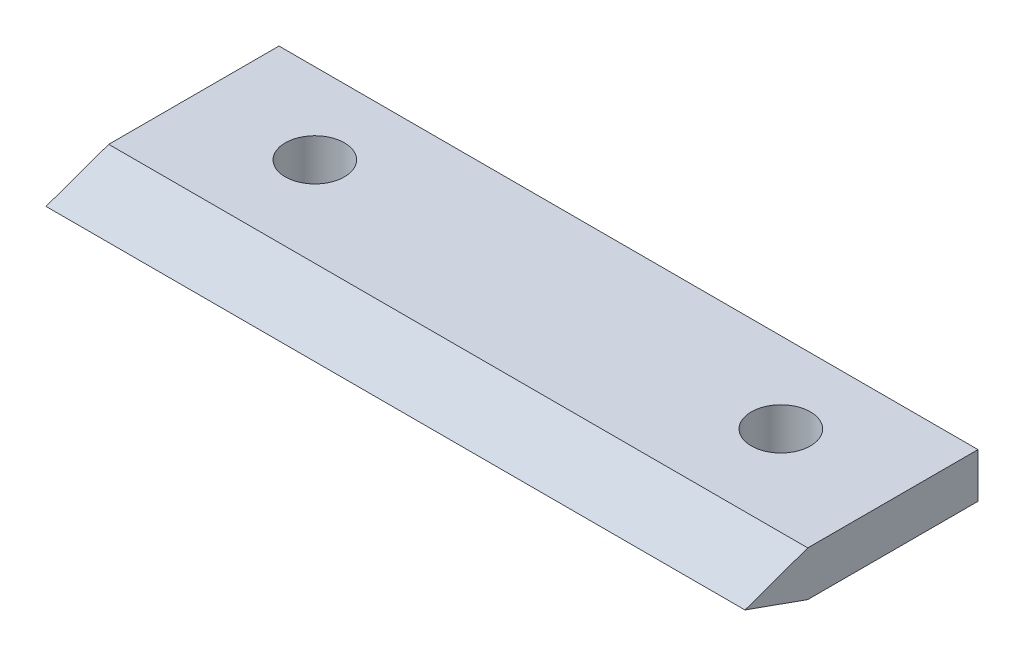
SolidWorks part; units mm, degrees
material "AISI 类型 A2 刀具钢"
ref_plane "前视基准面" through (0, 0, 0) normal (0, 0, 1) x (1, 0, 0)
ref_plane "上视基准面" through (0, 0, 0) normal (0, 1, 0) x (1, 0, 0)
ref_plane "右视基准面" through (0, 0, 0) normal (1, 0, 0) x (0, 0, -1)
sketch "草图1" plane through (0, 0, 0) normal (0, 1, 0) x (1, 0, 0)
  line L1 (0, 0) -> (39, 0)
  line L2 (0, 0) -> (0, 13)
  line L3 (0, 13) -> (39, 13)
  line L4 (39, 0) -> (39, 13)
  circle A0 centre (6.5, 8.5) radius 1.65
  circle A1 centre (32.5, 8.5) radius 1.65
  dimension "D7" = 3.3
  dimension "D3" = 3.3
  dimension "D4" = 6.5
  dimension "D5" = 6.5
  dimension "D1" = 26
  dimension "D2" = 13
  dimension "D8" = 4.5
extrude "凸台-拉伸1" add sketch "草图1" along normal blind 2.5
sketch "草图2" plane through (39, 0, 0) normal (1, 0, 0) x (0, 0, -1)
  line L0 (3.5, 2.5) -> (0, 2.5)
  line L1 (0, 2.5) -> (13, 2.5) construction
  line L2 (0, 2.5) -> (0, 1.25)
  line L3 (0, 2.5) -> (0, 0) construction
  line L4 (0, 1.25) -> (3.5, 2.5)
  dimension "D1" = 3.5
extrude "切除-拉伸1" cut sketch "草图2" against normal blind 42
sketch "草图3" plane through (39, 0, 0) normal (1, 0, 0) x (0, 0, -1)
  line L0 (0, 1.25) -> (0, 0)
  line L1 (0, 0) -> (3.5, 0)
  line L2 (0, 0) -> (13, 0) construction
  line L3 (3.5, 0) -> (0, 1.25)
  dimension "D1" = 3.5
extrude "切除-拉伸2" cut sketch "草图3" against normal blind 42
